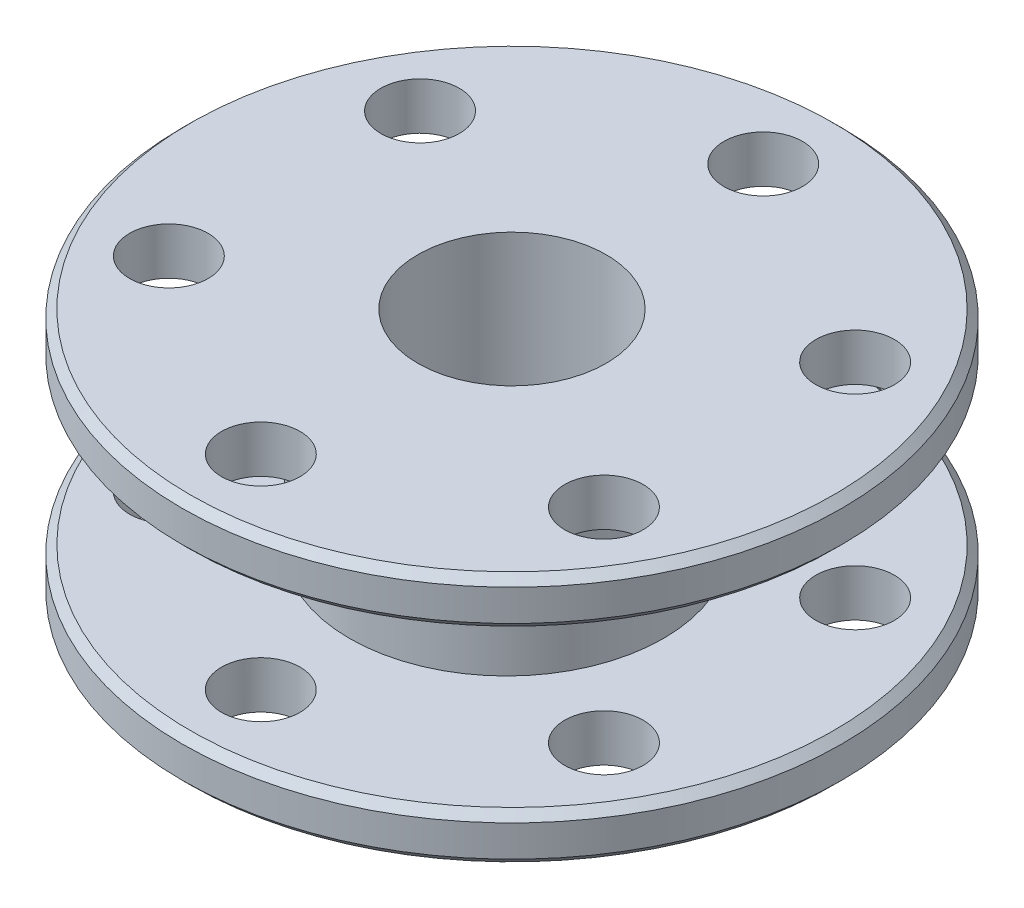
SolidWorks part; units mm, degrees
ref_plane "Front Plane" through (0, 0, 0) normal (0, 0, 1) x (1, 0, 0)
ref_plane "Top Plane" through (0, 0, 0) normal (0, 1, 0) x (1, 0, 0)
ref_plane "Right Plane" through (0, 0, 0) normal (1, 0, 0) x (0, 0, -1)
sketch "Sketch1" plane through (0, 0, 0) normal (0, 1, 0) x (1, 0, 0)
  circle A0 centre (0, 0) radius 21
  circle A1 centre (0, 0) radius 6
  circle A2 centre (0, 0) radius 16 construction
  circle A3 centre (0, 16) radius 2.5
  circle A4 centre (13.8564, 8) radius 2.5
  circle A5 centre (13.8564, -8) radius 2.5
  circle A6 centre (0, -16) radius 2.5
  circle A7 centre (-13.8564, -8) radius 2.5
  circle A8 centre (-13.8564, 8) radius 2.5
  point P20 (0, 0)
  dimension "D1" = 12
  dimension "D2" = 42
  dimension "D3" = 32
  dimension "D4" = 5
  dimension "D5" = 6
extrude "Boss-Extrude1" add sketch "Sketch1" along normal blind 16
sketch "Sketch2" plane through (0, 0, 0) normal (1, 0, 0) x (0, 0, -1)
  line L0 (-0.349, 0) -> (-0.349, 19.0272) construction
  line L1 (-21, 0) -> (21, 0) construction
  line L3 (9.651, 13) -> (27.754, 13)
  line L4 (9.651, 13) -> (9.651, 3)
  line L5 (9.651, 3) -> (27.754, 3)
  line L6 (27.754, 13) -> (27.754, 3)
  dimension "D1" = 3
  dimension "D2" = 3
  dimension "D3" = 10
revolve "Cut-Revolve1" cut sketch "Sketch2" angle 360 about L0
chamfer "Chamfer1" distance 0.5 angle 45 4 edges at (0, 0, 21) (0, 3, -21) (0, 16, 21) (0, 13, 21)
